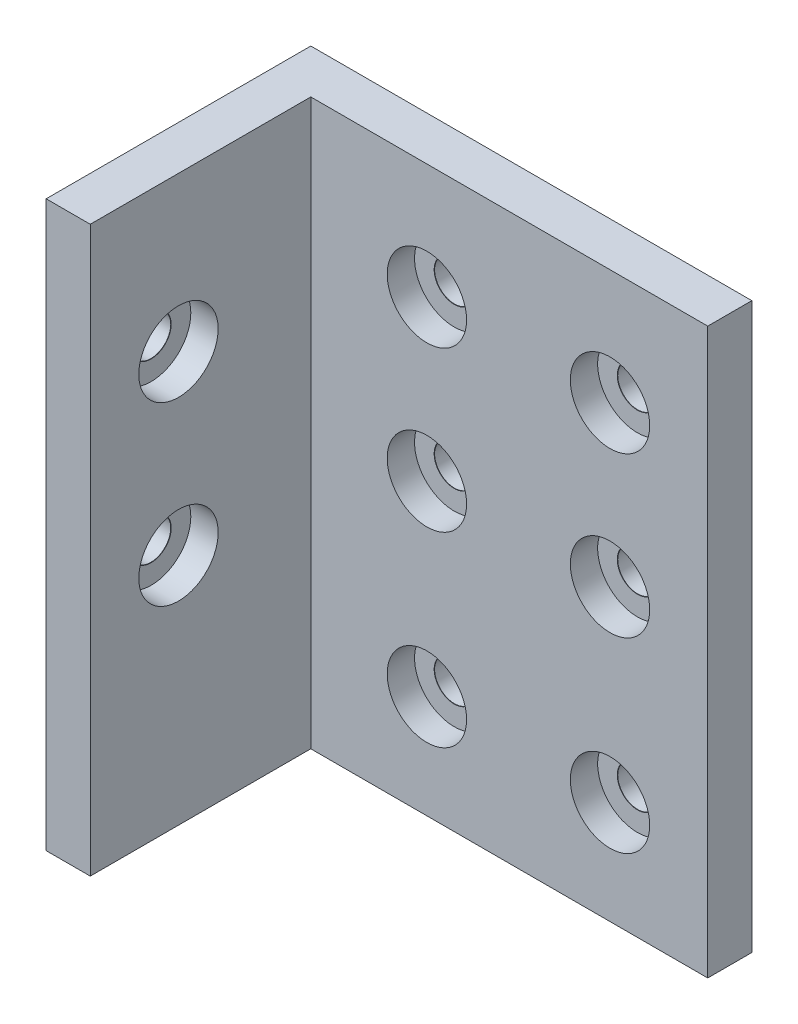
SolidWorks part; units mm, degrees
ref_plane "Plan de face" through (0, 0, 0) normal (0, 0, 1) x (1, 0, 0)
ref_plane "Plan de dessus" through (0, 0, 0) normal (0, 1, 0) x (1, 0, 0)
ref_plane "Plan de droite" through (0, 0, 0) normal (1, 0, 0) x (0, 0, -1)
sketch "Esquisse1" plane through (0, 0, 0) normal (0, 0, 1) x (1, 0, 0)
  line L1 (-25, -32) -> (25, -32)
  line L2 (-25, -32) -> (-25, 32)
  line L3 (-25, 32) -> (25, 32)
  line L4 (25, -32) -> (25, 32)
  line L5 (-25, -32) -> (25, 32) construction
  line L6 (-25, 32) -> (25, -32) construction
  point P0 (0, 0)
  dimension "D1" = 50
  dimension "D2" = 64
extrude "Boss.-Extru.1" add sketch "Esquisse1" along normal blind 30
sketch "Esquisse2" plane through (0, 32, 0) normal (0, 1, 0) x (1, 0, 0)
  line L8 (-20, -25) -> (20, -25)
  line L9 (20, -25) -> (20, -5)
  line L10 (20, -5) -> (-20, -5)
  line L11 (-20, -5) -> (-20, -25)
  line L12 (-20, -39.6044) -> (38.4438, -39.6044)
  line L13 (38.4438, -39.6044) -> (38.4438, -5)
  line L14 (38.4438, -5) -> (-20, -5)
  line L15 (-20, -5) -> (-20, -39.6044)
  dimension "D1" = 5
extrude "Enlèv. mat.-Extru.1" cut sketch "Esquisse2" against normal through all
hole_wizard "Dégagement M41" positions "Esquisse4" profile "Esquisse3" hole size "M4" standard "JIS" end condition through all
sketch "Esquisse4" plane through (0, 0, 0) normal (0, 0, -1) x (-1, 0, 0)
  point P0 (6.8387, 18.9372)
  point P2 (-13.9203, 18.9372)
  point P4 (-13.9203, 0.8631)
  point P6 (6.8387, 0.8631)
  point P8 (6.8387, -20.3015)
  point P10 (-13.9203, -20.3015)
sketch "Esquisse3" plane through (-6.8387, 18.9372, 0) normal (1, 0, 0) x (0, 1, 0)
  line L0 (0, 0) -> (0, 30)
  line L1 (0, 30) -> (2.25, 30)
  line L2 (2.25, 30) -> (2.25, 0)
  line L5 (2.25, 0) -> (0, 0)
  line L11 (0, -6.35) -> (0, 107.95) construction
  dimension "Diamètre du perçage jusqu'au prochain" = 4.5
  dimension "Profondeur du perçage jusqu'au prochain" = 30
hole_wizard "Dégagement M42" positions "Esquisse6" profile "Esquisse5" hole size "M4" standard "JIS" end condition through all
sketch "Esquisse6" plane through (-25, 0, 0) normal (-1, 0, 0) x (0, 0, 1)
  point P0 (20, 14.5)
  point P2 (20, -5.5)
sketch "Esquisse5" plane through (-25, 14.5, 20) normal (0, 1, 0) x (0, 0, 1)
  line L0 (0, 0) -> (0, 50)
  line L1 (0, 50) -> (2.25, 50)
  line L2 (2.25, 50) -> (2.25, 0)
  line L5 (2.25, 0) -> (0, 0)
  line L11 (0, -6.35) -> (0, 107.95) construction
  dimension "Diamètre du perçage jusqu'au prochain" = 4.5
  dimension "Profondeur du perçage jusqu'au prochain" = 50
hole_wizard "Chambrage pour vis à tête ronde bombée M41" positions "Esquisse8" profile "Esquisse7" counterbore size "M4" standard "Ansi Metric" end condition through all
sketch "Esquisse8" plane through (0, 0, 5) normal (0, 0, 1) x (1, 0, 0)
  point P0 (13.9203, 18.9372)
  point P3 (-6.8387, 18.9372)
  point P6 (13.9203, 0.8631)
  point P9 (-6.8387, 0.8631)
  point P12 (13.9203, -20.3015)
  point P15 (-6.8387, -20.3015)
sketch "Esquisse7" plane through (13.9203, 18.9372, 5) normal (1, 0, 0) x (0, -1, 0)
  line L0 (0, 0) -> (0, 5)
  line L1 (0, 5) -> (2.25, 5)
  line L2 (2.25, 3.125) -> (2.25, 5)
  line L3 (2.25, 3.125) -> (2.275, 3.1)
  line L4 (2.275, 3.1) -> (4.5, 3.1)
  line L5 (4.5, 3.1) -> (4.5, 0)
  line L7 (0, 0) -> (4.5, 0)
  line L9 (-2.25, 3.125) -> (-2.275, 3.1) construction
  line L11 (0, -6.35) -> (0, 107.95) construction
  dimension "Diamètre du perçage jusqu'au prochain" = 4.5
  dimension "Profondeur du perçage jusqu'au prochain" = 5
  dimension "Diamètre du chambrage" = 9
  dimension "Profondeur du chambrage" = 3.1
  dimension "Diamètre du fraisage milieu" = 4.55
  dimension "Angle du fraisage milieu" = 90
hole_wizard "Chambrage pour vis à tête ronde bombée M42" positions "Esquisse10" profile "Esquisse9" counterbore size "M4" standard "Ansi Metric" end condition through all
sketch "Esquisse10" plane through (-20, 0, 0) normal (1, 0, 0) x (0, 0, -1)
  point P0 (-20, 14.5)
  point P3 (-20, -5.5)
sketch "Esquisse9" plane through (-20, 14.5, 20) normal (0, 1, 0) x (0, 0, -1)
  line L0 (0, 0) -> (0, 5)
  line L1 (0, 5) -> (2.25, 5)
  line L2 (2.25, 3.125) -> (2.25, 5)
  line L3 (2.25, 3.125) -> (2.275, 3.1)
  line L4 (2.275, 3.1) -> (4.5, 3.1)
  line L5 (4.5, 3.1) -> (4.5, 0)
  line L7 (0, 0) -> (4.5, 0)
  line L9 (-2.25, 3.125) -> (-2.275, 3.1) construction
  line L11 (0, -6.35) -> (0, 107.95) construction
  dimension "Diamètre du perçage jusqu'au prochain" = 4.5
  dimension "Profondeur du perçage jusqu'au prochain" = 5
  dimension "Diamètre du chambrage" = 9
  dimension "Profondeur du chambrage" = 3.1
  dimension "Diamètre du fraisage milieu" = 4.55
  dimension "Angle du fraisage milieu" = 90
